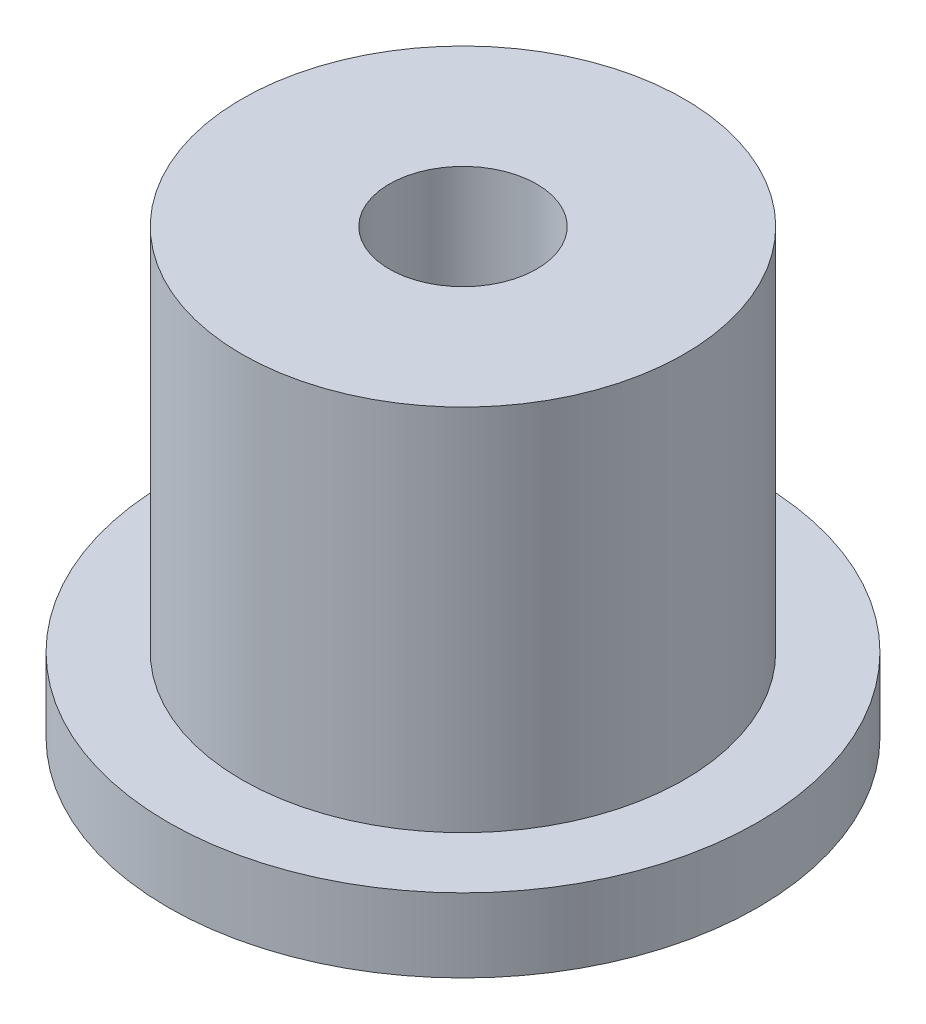
SolidWorks part; units mm, degrees
material "Commercial Bronze, UNS C22000 (90-10 Bronze)"
ref_plane "Front Plane" through (0, 0, 0) normal (0, 0, 1) x (1, 0, 0)
ref_plane "Top Plane" through (0, 0, 0) normal (0, 1, 0) x (1, 0, 0)
ref_plane "Right Plane" through (0, 0, 0) normal (1, 0, 0) x (0, 0, -1)
sketch "Sketch1" plane through (0, 0, 0) normal (0, 1, 0) x (1, 0, 0)
  circle A0 centre (0, 0) radius 25.4
  dimension "D1" = 50.8
extrude "Boss-Extrude1" add sketch "Sketch1" along normal blind 6.35
sketch "Sketch2" plane through (0, 6.35, 0) normal (0, 1, 0) x (1, 0, 0)
  circle A0 centre (0, 0) radius 19.05
  dimension "D1" = 38.1
extrude "Boss-Extrude2" add sketch "Sketch2" along normal blind 31.75
sketch "Sketch3" plane through (0, 0, 0) normal (0, -1, 0) x (1, 0, 0)
  circle A0 centre (0, 0) radius 6.35
  dimension "D1" = 12.7
extrude "Cut-Extrude1" cut sketch "Sketch3" against normal blind 38.1
